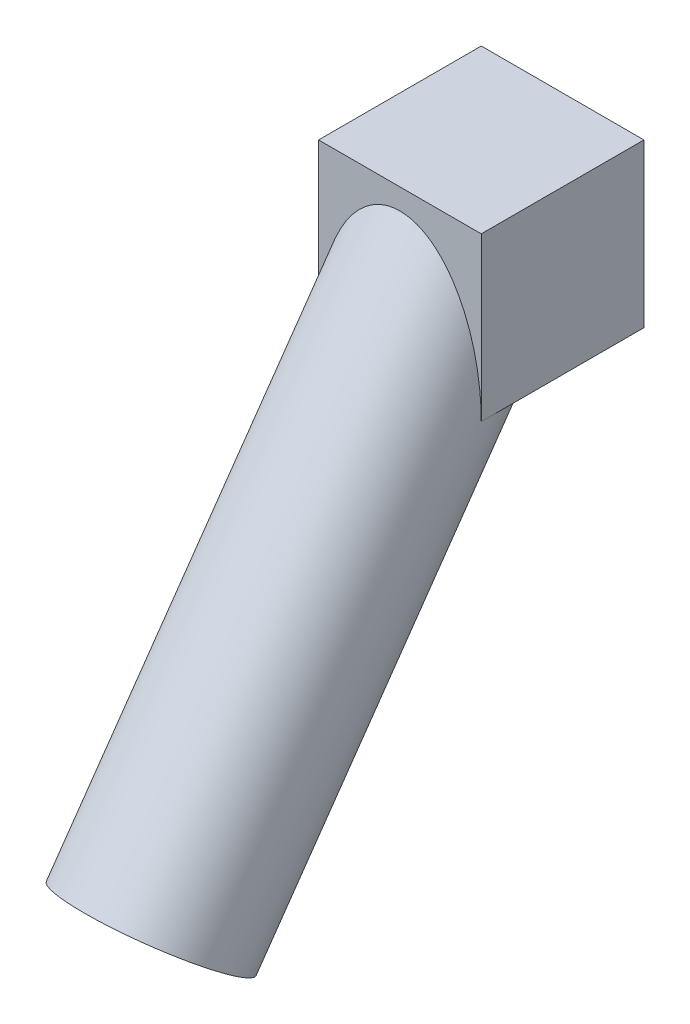
SolidWorks part; units mm, degrees
ref_plane "Front Plane" through (0, 0, 0) normal (0, 0, 1) x (1, 0, 0)
ref_plane "Top Plane" through (0, 0, 0) normal (0, 1, 0) x (1, 0, 0)
ref_plane "Right Plane" through (0, 0, 0) normal (1, 0, 0) x (0, 0, -1)
sketch "Sketch1" plane through (0, 0, 0) normal (0, 1, 0) x (1, 0, 0)
  line L1 (0, 0) -> (15, 0)
  line L2 (0, 0) -> (0, 15)
  line L3 (0, 15) -> (15, 15)
  line L4 (15, 0) -> (15, 15)
  dimension "D1" = 15
  dimension "D2" = 15
extrude "Boss-Extrude1" add sketch "Sketch1" along normal blind 15
ref_plane "Plane1" through (0, 0, 0) normal (0, -0.8192, 0.5736) x (1, 0, 0)
sketch "Sketch2" plane through (0, 0, 0) normal (0, -0.8192, 0.5736) x (1, 0, 0)
  line L0 (0, 0) -> (15, 0) construction
  circle A0 centre (7.5, 0) radius 7.5
extrude "Boss-Extrude2" add sketch "Sketch2" along normal blind 40 and the other way blind 12
